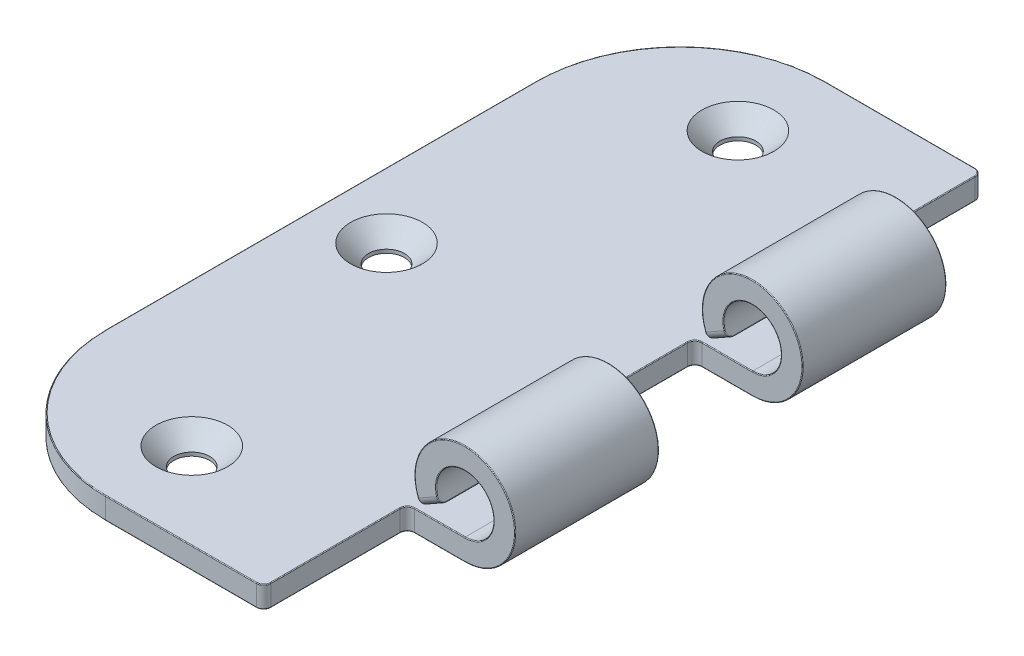
SolidWorks part; units mm, degrees
ref_plane "Front" through (0, 0, 0) normal (0, 0, 1) x (1, 0, 0)
ref_plane "Top" through (0, 0, 0) normal (0, 1, 0) x (1, 0, 0)
ref_plane "Right" through (0, 0, 0) normal (1, 0, 0) x (0, 0, -1)
sketch "Sketch1" plane through (0, 0, 0) normal (0, 0, 1) x (1, 0, 0)
  line L1 (0, -7) -> (-50, -7)
  line L2 (-50, -7) -> (-50, -4)
  line L3 (0, -4) -> (-50, -4)
  line L4 (-3.4801, -1.9721) -> (-6.0902, -3.4511)
  arc A0 (0, -4) -> (-3.4801, -1.9721) centre (0, 0) ccw
  arc A1 (0, -7) -> (-6.0902, -3.4511) centre (0, 0) ccw
  circle A3 centre (0, 0) radius 7 construction
  circle A4 centre (0, 0) radius 4 construction
  point P4 (3.8252, 1.1695)
  point P11 (7, 0)
  dimension "D1" = 8
  dimension "D3" = 50
  dimension "D2" = 3
extrude "Boss-Extrude1" add sketch "Sketch1" along normal blind 100
sketch "Sketch2" plane through (0, -4, 0) normal (0, 1, 0) x (1, 0, 0)
  line L0 (0, 0) -> (-50, 0) construction
  line L1 (-8, 0) -> (18.2321, 0)
  line L2 (-8, 0) -> (-8, -20)
  line L3 (-8, -20) -> (18.2321, -20)
  line L4 (18.2321, 0) -> (18.2321, -20)
  line L5 (7, -100) -> (7, 0) construction
  dimension "D1" = 15
  dimension "D2" = 20
extrude "Cut-Extrude1" cut sketch "Sketch2" against normal blind 52 and the other way blind 48
pattern_linear "LPattern1" count 6 spacing 40 along (0, 0, 1) of "Cut-Extrude1"
fillet "Fillet1" radius 1 1 edges at (-8, -5.5, 80)
fillet "Fillet2" radius 1 3 edges at (-8, -5.5, 20) (-8, -5.5, 40) (-8, -5.5, 60)
sketch "Sketch3" plane through (0, -4, 0) normal (0, 1, 0) x (1, 0, 0)
  circle A0 centre (-30, -12) radius 2.5
  circle A1 centre (-40.8984, -50) radius 2.5
  circle A2 centre (-30, -88) radius 2.5
  dimension "D1" = 5
extrude "Cut-Extrude2" cut sketch "Sketch3" against normal blind 10
chamfer "Chamfer1" distance 2.5 angle 45 3 edges at (-30, -4, 85.5) (-40.8984, -4, 52.5) (-30, -4, 14.5)
fillet "Fillet3" radius 20 2 edges at (-50, -5.5, 0) (-50, -5.5, 100)
fillet "Fillet4" radius 1 6 edges at (-4.7851, -2.7116, 80) (-4.7851, -2.7116, 60) (-4.7851, -2.7116, 40) (-4.7851, -2.7116, 20) (-8, -5.5, 0) (-8, -5.5, 100)
fillet "Fillet5" radius 0.1 56 edges at (-44.1421, -7, 94.1421) (-50, -7, 50) (-44.1421, -7, 5.8579) (-19.5, -7, 0) (-8.2929, -7, 0.2929) (-8, -7, 10) (-7.7071, -7, 19.7071) (-3.5, -7, 20) (3.9484, 5.7801, 20) (-6.2677, -3.1171, 20.2169) (-6.0902, -3.4511, 30) (-6.1952, -3.2588, 39.6246) (3.9484, 5.7801, 40) (-3.5, -7, 40) (-7.7071, -7, 40.2929) (-8, -7, 50) (-7.7071, -7, 59.7071) (-3.5, -7, 60) (3.9484, 5.7801, 60) (-6.2677, -3.1171, 60.2169) (-6.0902, -3.4511, 70) (-6.1952, -3.2588, 79.6246) (3.9484, 5.7801, 80) (-3.5, -7, 80) (-7.7071, -7, 80.2929) (-8, -7, 90) (-8.2929, -7, 99.7071) (-8.2929, -4, 99.7071) (-8, -4, 90) (-7.7071, -4, 80.2929) (-3.5, -4, 80) (2.4333, 3.1747, 80) (-3.6533, -1.6289, 79.7877) (-3.4801, -1.9721, 70) (-3.5828, -1.7787, 60.3756) (2.4333, 3.1747, 60) (-3.5, -4, 60) (-7.7071, -4, 59.7071) (-8, -4, 50) (-7.7071, -4, 40.2929) (-3.5, -4, 40) (2.4333, 3.1747, 40) (-3.6533, -1.6289, 39.7877) (-3.4801, -1.9721, 30) (-3.5828, -1.7787, 20.3756) (2.4333, 3.1747, 20) (-3.5, -4, 20) (-7.7071, -4, 19.7071) (-8, -4, 10) (-8.2929, -4, 0.2929) (-19.5, -4, 0) (-44.1421, -4, 5.8579) (-50, -4, 50) (-44.1421, -4, 94.1421) (-19.5, -7, 100) (-19.5, -4, 100)
